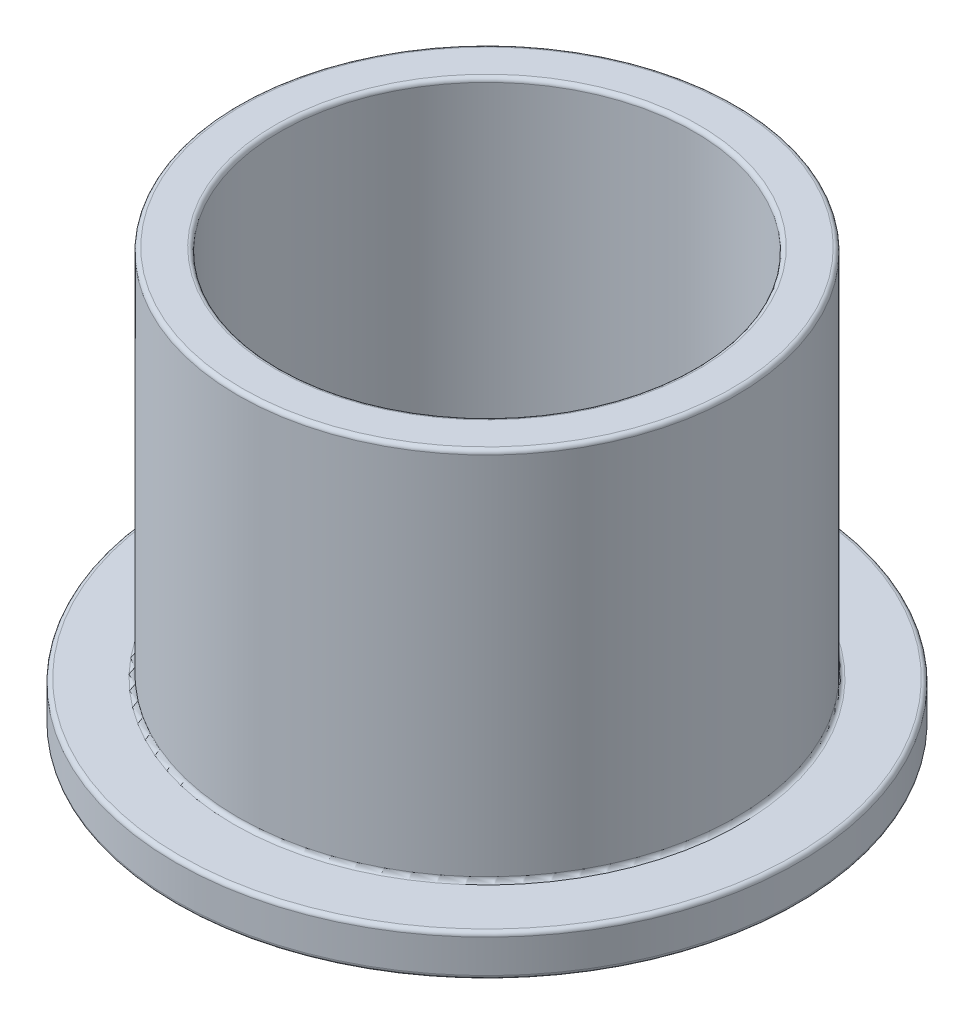
SolidWorks part; units mm, degrees
ref_plane "Front" through (0, 0, 0) normal (0, 0, 1) x (1, 0, 0)
ref_plane "Top" through (0, 0, 0) normal (0, 1, 0) x (1, 0, 0)
ref_plane "Right" through (0, 0, 0) normal (1, 0, 0) x (0, 0, -1)
sketch "Sketch1" plane through (0, 0, 0) normal (0, 1, 0) x (1, 0, 0)
  circle A0 centre (0, 0) radius 4
  circle A1 centre (0, 0) radius 4.8
  circle A2 centre (0, 0) radius 6
  dimension "ID" = 8
  dimension "OD" = 9.6
  dimension "FlangeOD" = 12
sketch "Sketch2" plane through (0, 0, 0) normal (1, 0, 0) x (0, 0, -1)
  line L0 (6, 0) -> (6, 0.8) construction
  line L1 (-4.8, 0) -> (-4.8, 8) construction
  line L8 (0, 0) -> (0, 8) construction
  point P5 (-6, 0)
  dimension "Flange Thickness" = 0.8
  dimension "Length" = 8
sketch "Sketch3" plane through (0, 0, 0) normal (0, 1, 0) x (1, 0, 0)
  circle A0 centre (0, 0) radius 4 construction
  circle A1 centre (0, 0) radius 4.8 construction
  circle A2 centre (0, 0) radius 4
  circle A3 centre (0, 0) radius 4.8
extrude "Boss-Extrude1" add sketch "Sketch3" along normal up to vertex (8 mm away) up to point (0, 8, 4.8)
sketch "Sketch4" plane through (0, 0, 0) normal (0, 1, 0) x (1, 0, 0)
  circle A0 centre (0, 0) radius 6 construction
  circle A1 centre (0, 0) radius 4.8 construction
  circle A2 centre (0, 0) radius 6
  circle A3 centre (0, 0) radius 4.8
extrude "Boss-Extrude2" add sketch "Sketch4" along normal up to vertex (0.8 mm away) up to point (0, 0.8, -6)
fillet "Fillet1" radius 0.08 6 edges at (0, 0, 4) (0, 0, 6) (0, 0.8, 4.8) (0, 0.8, 6) (0, 8, 4) (0, 8, 4.8)
equation "\"D1@Fillet1\"=(\"OD@Sketch1\"-\"ID@Sketch1\")*.05"
